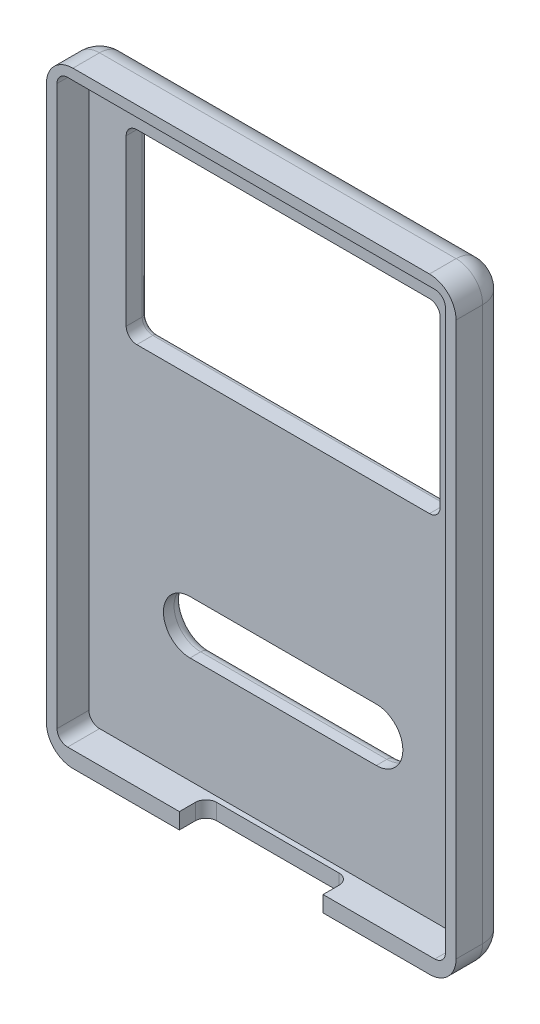
SolidWorks part; units mm, degrees
ref_plane "Front Plane" through (0, 0, 0) normal (0, 0, 1) x (1, 0, 0)
ref_plane "Top Plane" through (0, 0, 0) normal (0, 1, 0) x (1, 0, 0)
ref_plane "Right Plane" through (0, 0, 0) normal (1, 0, 0) x (0, 0, -1)
sketch "Sketch1" plane through (0, 0, 0) normal (0, 0, 1) x (1, 0, 0)
  line L1 (0, 108.8169) -> (77, 108.8169)
  line L2 (0, 108.8169) -> (0, -5.1831)
  line L3 (0, -5.1831) -> (77, -5.1831)
  line L4 (77, 108.8169) -> (77, -5.1831)
  dimension "D1" = 77
  dimension "D2" = 114
extrude "Boss-Extrude1" add sketch "Sketch1" along normal blind 10
sketch "Sketch2" plane through (0, 0, 10) normal (0, 0, 1) x (1, 0, 0)
  line L0 (77, -5.1831) -> (77, 108.8169) construction
  line L1 (2, 106.8169) -> (75, 106.8169)
  line L2 (2, 106.8169) -> (2, -2.1831)
  line L3 (2, -2.1831) -> (75, -2.1831)
  line L4 (75, 106.8169) -> (75, -2.1831)
  line L5 (0, 108.8169) -> (0, -5.1831) construction
  line L6 (0, -5.1831) -> (77, -5.1831) construction
  line L7 (77, 108.8169) -> (0, 108.8169) construction
  dimension "D1" = 2
  dimension "D2" = 2
  dimension "D3" = 3
  dimension "D4" = 2
extrude "Cut-Extrude1" cut sketch "Sketch2" against normal blind 6
sketch "Sketch3" plane through (0, 0, 4) normal (0, 0, 1) x (1, 0, 0)
  line L0 (75, -2.1831) -> (75, 106.8169) construction
  line L1 (9, 98.8169) -> (68, 98.8169)
  line L2 (9, 98.8169) -> (9, 63.8169)
  line L3 (9, 63.8169) -> (68, 63.8169)
  line L4 (68, 98.8169) -> (68, 63.8169)
  line L6 (77, 108.8169) -> (0, 108.8169) construction
  line L7 (2, 106.8169) -> (2, -2.1831) construction
  dimension "D1" = 7
  dimension "D2" = 7
  dimension "D3" = 10
  dimension "D4" = 35
extrude "Cut-Extrude2" cut sketch "Sketch3" against normal blind 6
fillet "Fillet1" radius 5 4 edges at (0, -5.1831, 5) (77, -5.1831, 5) (0, 108.8169, 5) (77, 108.8169, 5)
fillet "Fillet2" radius 5 8 edges at (1.4645, 107.3525, 0) (38.5, 108.8169, 0) (75.5355, 107.3525, 0) (77, 51.8169, 0) (75.5355, -3.7186, 0) (38.5, -5.1831, 0) (1.4645, -3.7186, 0) (0, 51.8169, 0)
fillet "Fillet3" radius 2 4 edges at (68, 63.8169, 2) (9, 63.8169, 2) (9, 98.8169, 2) (68, 98.8169, 2)
fillet "Fillet4" radius 2 4 edges at (75, 106.8169, 7) (75, -2.1831, 7) (2, -2.1831, 7) (2, 106.8169, 7)
sketch "Sketch7" plane through (0, -5.1831, 0) normal (0, -1, 0) x (1, 0, 0)
  line L0 (5, 10) -> (72, 10) construction
  line L1 (25, 10) -> (52, 10)
  line L2 (25, 10) -> (25, 5)
  line L3 (25, 5) -> (52, 5)
  line L4 (52, 10) -> (52, 5)
  line L5 (5, 5) -> (72, 5) construction
  line L6 (72, 5) -> (72, 10) construction
  line L7 (5, 10) -> (5, 5) construction
  dimension "D1" = 20
  dimension "D2" = 20
  dimension "D3" = 5
extrude "Cut-Extrude8" cut sketch "Sketch7" against normal blind 6
fillet "Fillet5" radius 2 2 edges at (25, -3.6831, 5) (52, -3.6831, 5)
sketch "Sketch8" plane through (0, 0, 0) normal (0, 0, -1) x (-1, 0, 0)
  line L0 (-56, 22.8169) -> (-21, 22.8169) construction
  line L1 (-56, 27.8169) -> (-21, 27.8169)
  line L2 (-56, 17.8169) -> (-21, 17.8169)
  line L3 (-72, 103.8169) -> (-72, -0.1831) construction
  line L4 (-5, -0.1831) -> (-5, 103.8169) construction
  line L5 (-72, -0.1831) -> (-5, -0.1831) construction
  arc A0 (-56, 27.8169) -> (-56, 17.8169) centre (-56, 22.8169) ccw
  arc A1 (-21, 17.8169) -> (-21, 27.8169) centre (-21, 22.8169) ccw
  point P2 (-38.5, 22.8169)
  dimension "D2" = 35
  dimension "D3" = 16
  dimension "D4" = 16
  dimension "D1" = 10
  dimension "D5" = 18
extrude "Cut-Extrude9" cut sketch "Sketch8" against normal blind 10
fillet "Fillet6" radius 2 4 edges at (61, 22.8169, 0) (38.5, 27.8169, 0) (16, 22.8169, 0) (38.5, 17.8169, 0)
fillet "Fillet7" radius 1 8 edges at (67.4142, 64.4027, 0) (38.5, 63.8169, 0) (9.5858, 64.4027, 0) (9, 81.3169, 0) (9.5858, 98.2311, 0) (38.5, 98.8169, 0) (67.4142, 98.2311, 0) (68, 81.3169, 0)
